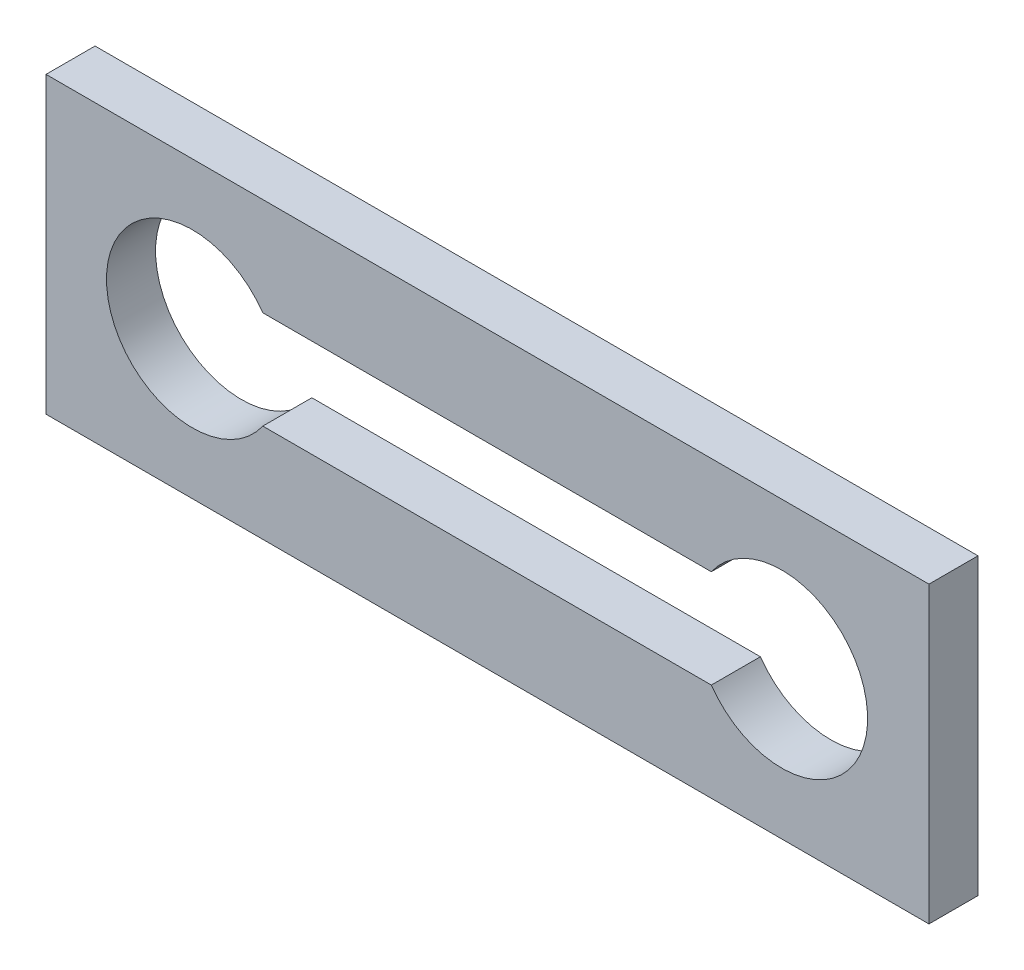
SolidWorks part; units mm, degrees
ref_plane "Front Plane" through (0, 0, 0) normal (0, 0, 1) x (1, 0, 0)
ref_plane "Top Plane" through (0, 0, 0) normal (0, 1, 0) x (1, 0, 0)
ref_plane "Right Plane" through (0, 0, 0) normal (1, 0, 0) x (0, 0, -1)
sketch "Sketch1" plane through (0, 0, 0) normal (0, 0, 1) x (1, 0, 0)
  line L1 (-57.15, -19.05) -> (57.15, -19.05)
  line L2 (-57.15, -19.05) -> (-57.15, 19.05)
  line L3 (-57.15, 19.05) -> (57.15, 19.05)
  line L4 (57.15, -19.05) -> (57.15, 19.05)
  line L5 (-57.15, -19.05) -> (57.15, 19.05) construction
  line L6 (-57.15, 19.05) -> (57.15, -19.05) construction
  point P0 (0, 0)
  dimension "D1" = 38.1
  dimension "D2" = 114.3
extrude "Boss-Extrude1" add sketch "Sketch1" along normal blind 6.35
sketch "Sketch2" plane through (0, 0, 6.35) normal (0, 0, 1) x (1, 0, 0)
  line L0 (0, 0) -> (-38.2053, 0) construction
  line L1 (0, 0) -> (38.1, 0) construction
  circle A0 centre (-38.2053, 0) radius 11.1125
  circle A1 centre (38.1, 0) radius 11.1125
  dimension "D3" = 22.225
  dimension "D4" = 22.225
  dimension "D1" = 38.2053
  dimension "D2" = 38.1
extrude "Cut-Extrude1" cut sketch "Sketch2" against normal through all
sketch "Sketch3" plane through (0, 0, 6.35) normal (0, 0, 1) x (1, 0, 0)
  line L1 (33.272, -6.35) -> (-33.272, -6.35)
  line L2 (33.272, -6.35) -> (33.272, 6.35)
  line L3 (33.272, 6.35) -> (-33.272, 6.35)
  line L4 (-33.272, -6.35) -> (-33.272, 6.35)
  line L5 (33.272, -6.35) -> (-33.272, 6.35) construction
  line L6 (33.272, 6.35) -> (-33.272, -6.35) construction
  point P0 (0, 0)
  dimension "D1" = 12.7
extrude "Cut-Extrude2" cut sketch "Sketch3" against normal through all
